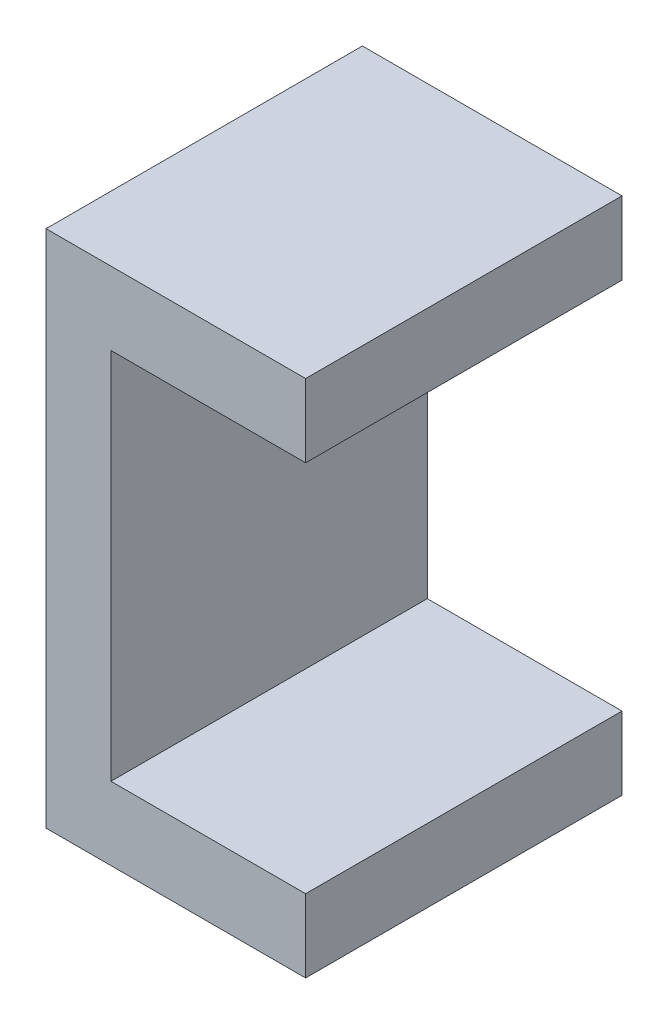
SolidWorks part; units mm, degrees
ref_plane "Front Plane" through (0, 0, 0) normal (0, 0, 1) x (1, 0, 0)
ref_plane "Top Plane" through (0, 0, 0) normal (0, 1, 0) x (1, 0, 0)
ref_plane "Right Plane" through (0, 0, 0) normal (1, 0, 0) x (0, 0, -1)
sketch "Sketch1" plane through (0, 0, 0) normal (0, 0, 1) x (1, 0, 0)
  line L1 (-10, -16) -> (-6, -16)
  line L2 (-10, -16) -> (-10, 16)
  line L3 (-10, 16) -> (-6, 16)
  line L4 (-6, -11.5) -> (-6, 11.5)
  line L5 (-6, 16) -> (6, 16)
  line L7 (-6, 11.5) -> (6, 11.5)
  line L8 (6, 16) -> (6, 11.5)
  line L9 (-6, -16) -> (6, -16)
  line L11 (-6, -11.5) -> (6, -11.5)
  line L12 (6, -16) -> (6, -11.5)
  point P10 (-6, 0)
  point P12 (0, 11.5)
  dimension "D1" = 12
  dimension "D2" = 32
  dimension "D3" = 4.5
  dimension "D4" = 12
  dimension "D5" = 4.5
  dimension "D6" = 4
extrude "Boss-Extrude1" add sketch "Sketch1" along normal blind 19.5
